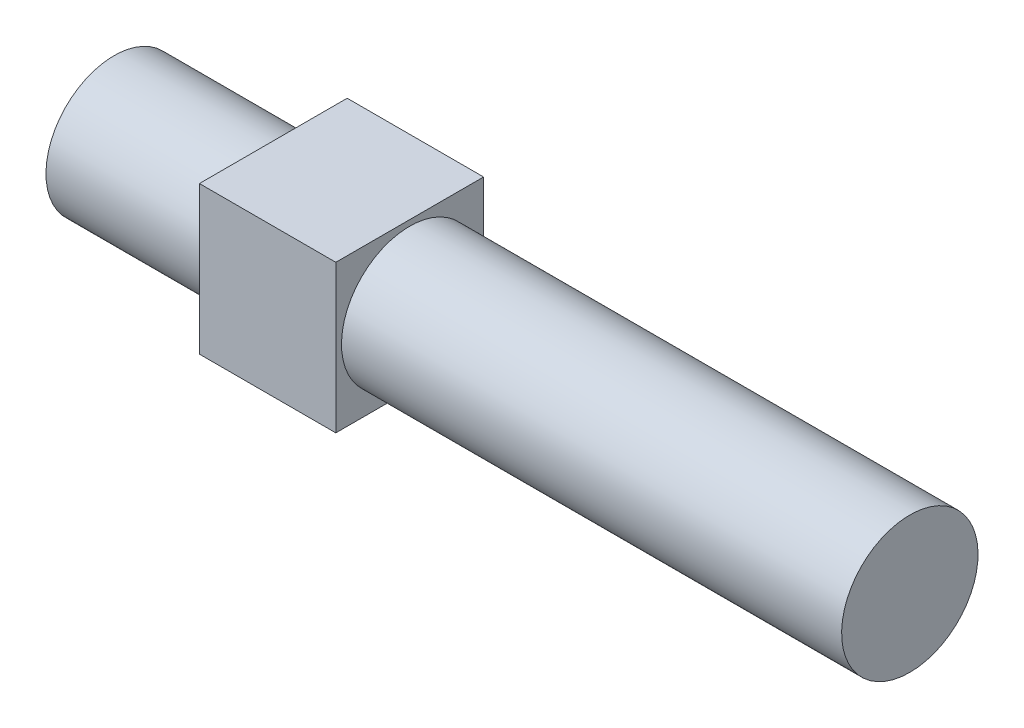
SolidWorks part; units mm, degrees
ref_plane "Front Plane" through (0, 0, 0) normal (0, 0, 1) x (1, 0, 0)
ref_plane "Top Plane" through (0, 0, 0) normal (0, 1, 0) x (1, 0, 0)
ref_plane "Right Plane" through (0, 0, 0) normal (1, 0, 0) x (0, 0, -1)
sketch "Sketch1" plane through (0, 0, 0) normal (0, 0, 1) x (1, 0, 0)
  line L0 (0, 0) -> (70, 0)
  line L1 (70, 0) -> (70, -6)
  line L3 (0, -6) -> (0, 0)
  line L4 (0, -6) -> (70, -6)
  dimension "D1" = 70
  dimension "D2" = 6
revolve "Revolve1" add sketch "Sketch1" angle 360 about L4
ref_plane "Plane1" through (14, 0, 0) normal (1, 0, 0) x (0, 0, -1)
sketch "Sketch2" plane through (14, 0, 0) normal (1, 0, 0) x (0, 0, -1)
  line L1 (-6.5, 0.5) -> (6.5, 0.5)
  line L2 (-6.5, 0.5) -> (-6.5, -12.5)
  line L3 (-6.5, -12.5) -> (6.5, -12.5)
  line L4 (6.5, 0.5) -> (6.5, -12.5)
  line L5 (-6.5, 0.5) -> (6.5, -12.5) construction
  line L6 (-6.5, -12.5) -> (6.5, 0.5) construction
  point P0 (0, -6)
  dimension "D1" = 13
extrude "Boss-Extrude1" add sketch "Sketch2" along normal blind 12
